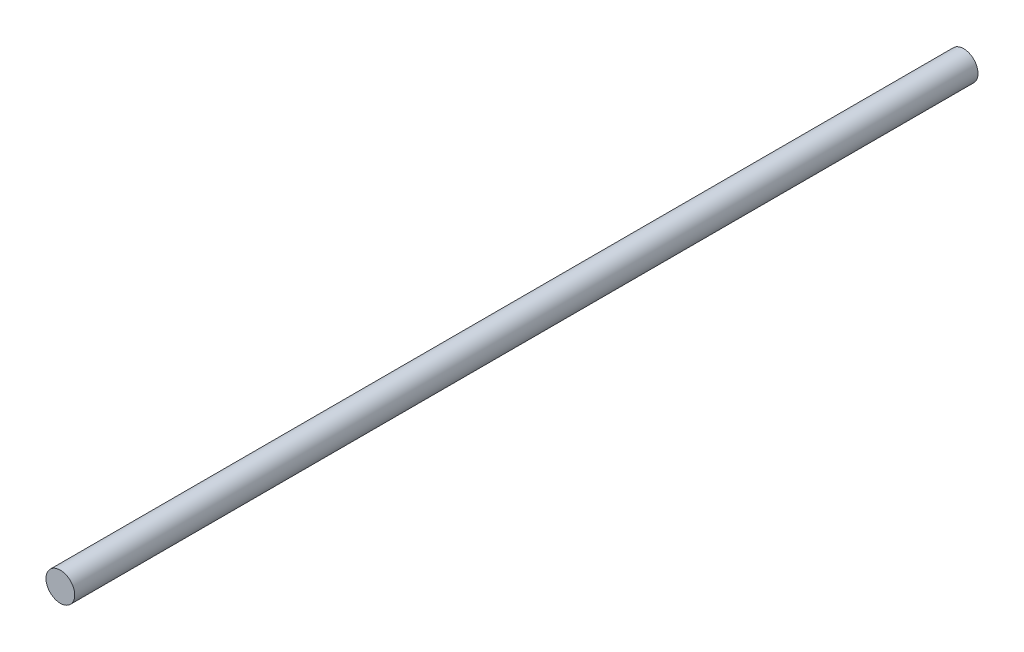
SolidWorks part; units mm, degrees
ref_plane "Front Plane" through (0, 0, 0) normal (0, 0, 1) x (1, 0, 0)
ref_plane "Top Plane" through (0, 0, 0) normal (0, 1, 0) x (1, 0, 0)
ref_plane "Right Plane" through (0, 0, 0) normal (1, 0, 0) x (0, 0, -1)
sketch "Sketch1" plane through (0, 0, 0) normal (0, 0, 1) x (1, 0, 0)
  circle A0 centre (0, 0) radius 3.175
  dimension "D1" = 6.35
extrude "Boss-Extrude1" add sketch "Sketch1" against normal blind 199.644
